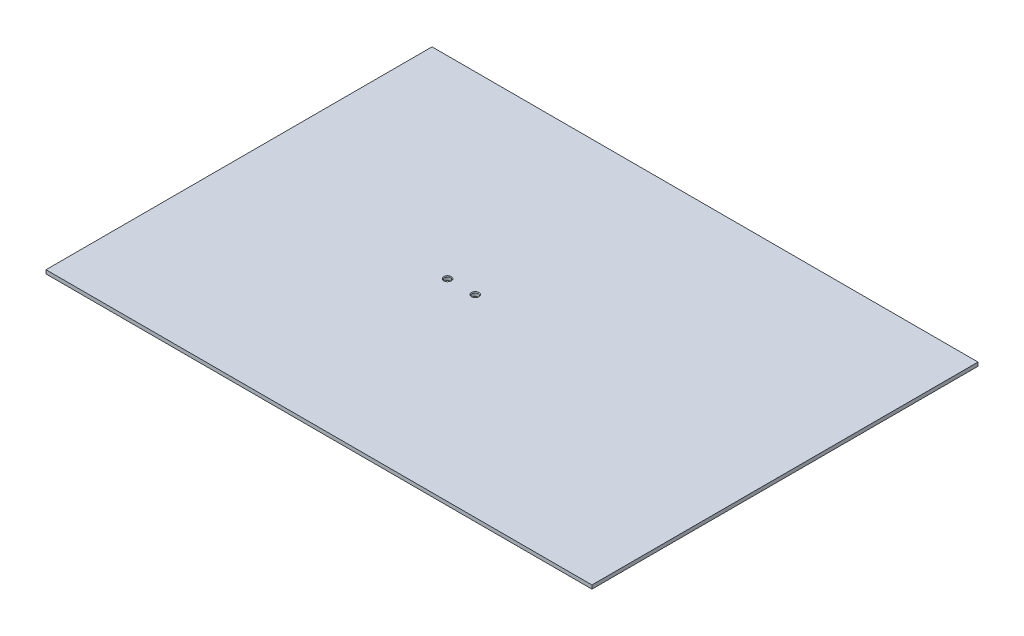
SolidWorks part; units mm, degrees
ref_plane "Front Plane" through (0, 0, 0) normal (0, 0, 1) x (1, 0, 0)
ref_plane "Top Plane" through (0, 0, 0) normal (0, 1, 0) x (1, 0, 0)
ref_plane "Right Plane" through (0, 0, 0) normal (1, 0, 0) x (0, 0, -1)
sketch "Sketch1" plane through (0, 0, 0) normal (0, 1, 0) x (1, 0, 0)
  line L1 (-148.5, -105) -> (148.5, -105)
  line L2 (-148.5, -105) -> (-148.5, 105)
  line L3 (-148.5, 105) -> (148.5, 105)
  line L4 (148.5, -105) -> (148.5, 105)
  line L5 (-148.5, -105) -> (148.5, 105) construction
  line L6 (-148.5, 105) -> (148.5, -105) construction
  point P0 (0, 0)
  dimension "D1" = 210
  dimension "D2" = 297
extrude "Boss-Extrude1" add sketch "Sketch1" along normal blind 2
sketch "Sketch3" plane through (0, 2, 0) normal (0, 1, 0) x (1, 0, 0)
  line L0 (-148.5, 0) -> (148.5, 0) construction
  line L1 (148.5, -105) -> (148.5, 105) construction
  line L3 (-40, -6.35) -> (40, -6.35) construction
  line L4 (-40, -6.35) -> (-40, 6.35) construction
  line L5 (-40, 6.35) -> (40, 6.35) construction
  line L6 (40, -6.35) -> (40, 6.35) construction
  line L7 (-40, -6.35) -> (40, 6.35) construction
  line L8 (-40, 6.35) -> (40, -6.35) construction
  line L9 (-15, -6.35) -> (-40, -6.35)
  line L10 (-15, -6.35) -> (-15, 6.35)
  line L11 (-15, 6.35) -> (-40, 6.35)
  line L12 (-40, -6.35) -> (-40, 6.35)
  line L13 (-15, -6.35) -> (-40, 6.35) construction
  line L14 (-15, 6.35) -> (-40, -6.35) construction
  point P0 (-27.5, 0)
  point P6 (0, 0)
  point P8 (-20, 0)
  point P9 (-35, 0)
  point P11 (0, 0)
  dimension "D1" = 12.7
  dimension "D2" = 80
  dimension "D3" = 5
  dimension "D4" = 20
  dimension "D5" = 5
sketch "Sketch5" plane through (0, 2, 0) normal (0, 1, 0) x (1, 0, 0)
  point P0 (-20, 0)
  point P1 (-35, 0)
hole_wizard "M4 Tapped Hole1" positions "Sketch5" profile "Sketch6" tap size "M4" standard "ISO" end condition through all
sketch "Sketch6" plane through (-20, 2, 0) normal (1, 0, 0) x (0, 0, 1)
  line L0 (0, 0) -> (0, 2)
  line L1 (0, 2) -> (1.65, 2)
  line L2 (1.65, 2) -> (1.65, 0.375)
  line L3 (1.65, 0.375) -> (2.025, 0)
  line L5 (2.025, 0) -> (0, 0)
  line L6 (-1.65, 0.375) -> (-2.025, 0) construction
  line L11 (0, -6.35) -> (0, 107.95) construction
  dimension "Thru Tap Drill Dia." = 3.3
  dimension "Thru Tap Drill Depth" = 2
  dimension "Near C'Sink Dia." = 4.05
  dimension "Near C'Sink Angle" = 90
cosmetic thread "Hole Thread1" parameters "D2"=4
cosmetic thread "Hole Thread2" parameters "D2"=4
equation "\"l\"= 297mm"
equation "\"w\"= 210mm"
equation "\"D1@Sketch1\"=\"w\""
equation "\"l2\"= ( ( \"l\" / 2 ) - 1 )"
